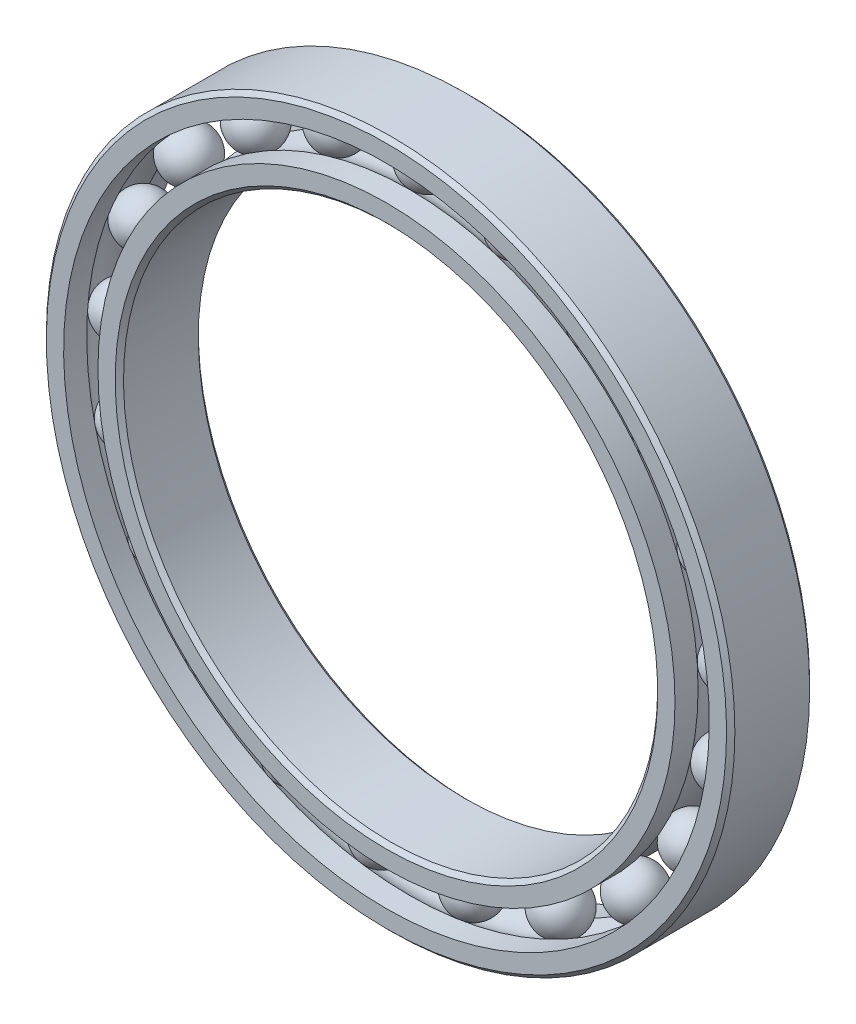
SolidWorks part; units mm, degrees
ref_plane "Front Plane" through (0, 0, 0) normal (0, 0, 1) x (1, 0, 0)
ref_plane "Top Plane" through (0, 0, 0) normal (0, 1, 0) x (1, 0, 0)
ref_plane "Right Plane" through (0, 0, 0) normal (1, 0, 0) x (0, 0, -1)
sketch "Sketch1" plane through (0, 0, 0) normal (0, 0, 1) x (1, 0, 0)
  circle A0 centre (0, 0) radius 29
  circle A1 centre (0, 0) radius 22.5
  dimension "OD" = 58
  dimension "ID" = 45
  dimension "For Shaft Diameter" = 45
  dimension "For Housing ID" = 58
sketch "Sketch5" plane through (0, 0, 0) normal (1, 0, 0) x (0, 0, -1)
  line L0 (-3.5, 0) -> (3.5, 0) construction
  line L1 (0, 29) -> (0, -29) construction
  line L2 (3.15, 29) -> (-3.15, 29)
  line L3 (-3.15, 29) -> (-3.5, 28.65)
  line L4 (-3.5, 28.65) -> (-3.5, 27.1944)
  line L5 (-3.5, 27.1944) -> (-1.5556, 27.1944)
  line L6 (3.5, 27.1944) -> (1.5556, 27.1944)
  line L7 (3.5, 28.65) -> (3.5, 27.1944)
  line L8 (3.15, 29) -> (3.5, 28.65)
  line L9 (0, 29) -> (0, 25.75) construction
  line L10 (0, 25.75) -> (0, 22.5) construction
  line L11 (-2.1228, 25.75) -> (-3.5, 25.75) construction
  line L12 (2.6209, 24.331) -> (3.0019, 24.331) construction
  line L13 (-2.6209, 24.331) -> (-3.0019, 24.331) construction
  line L14 (-2.6209, 24.331) -> (-2.6209, 27.169) construction
  line L15 (-2.6209, 27.169) -> (-3.0019, 27.169) construction
  line L16 (-3.0019, 24.331) -> (-3.0019, 27.169) construction
  line L17 (-2.6209, 24.331) -> (-3.0019, 27.169) construction
  line L18 (-2.6209, 27.169) -> (-3.0019, 24.331) construction
  line L19 (3.0019, 24.331) -> (3.0019, 27.169) construction
  line L20 (2.6209, 27.169) -> (3.0019, 27.169) construction
  line L21 (2.6209, 24.331) -> (2.6209, 27.169) construction
  line L22 (0, 29) -> (0, -29) construction
  arc A0 (-1.5556, 27.1944) -> (1.5556, 27.1944) centre (0, 25.75) cw
  circle A1 centre (0, 25.75) radius 2.1228 construction
  point P14 (0, 22.5)
  point P15 (-2.8114, 25.75)
  dimension "D1" = 45
  dimension "D2" = 0.35
  dimension "D3" = 3.1111
  dimension "D4" = 1.4444
  dimension "D5" = 0.381
  dimension "D6" = 0.0254
  dimension "Width" = 7
sketch "Sketch6" plane through (0, 0, 0) normal (1, 0, 0) x (0, 0, -1)
  line L0 (3.15, 29) -> (3.5, 28.65) construction
  line L1 (3.5, 28.65) -> (3.5, 27.1944) construction
  line L2 (3.5, 27.1944) -> (1.5556, 27.1944) construction
  line L3 (-3.5, 27.1944) -> (-1.5556, 27.1944) construction
  line L4 (-3.5, 28.65) -> (-3.5, 27.1944) construction
  line L5 (-3.15, 29) -> (-3.5, 28.65) construction
  line L6 (3.15, 29) -> (-3.15, 29) construction
  line L7 (3.15, 29) -> (3.5, 28.65)
  line L8 (3.5, 28.65) -> (3.5, 27.1944)
  line L9 (3.5, 27.1944) -> (1.5556, 27.1944)
  line L10 (-3.5, 27.1944) -> (-1.5556, 27.1944)
  line L11 (-3.5, 28.65) -> (-3.5, 27.1944)
  line L12 (-3.15, 29) -> (-3.5, 28.65)
  line L13 (3.15, 29) -> (-3.15, 29)
  arc A0 (1.5556, 27.1944) -> (-1.5556, 27.1944) centre (0, 25.75) ccw construction
  arc A1 (1.5556, 27.1944) -> (-1.5556, 27.1944) centre (0, 25.75) ccw
revolve "Revolve5" add sketch "Sketch6" angle 360 about L0
sketch "Sketch3" plane through (0, 0, 0) normal (1, 0, 0) x (0, 0, -1)
  line L0 (-3.5, 24.3056) -> (-1.5556, 24.3056)
  line L1 (0, 29) -> (0, -29) construction
  line L2 (-3.5, 28.65) -> (-3.5, 27.1944) construction
  line L3 (-3.5, 24.3056) -> (-3.5, 22.85)
  line L4 (-3.15, 29) -> (-3.5, 28.65) construction
  line L5 (-3.5, 22.85) -> (-3.15, 22.5)
  line L6 (-3.15, 22.5) -> (3.15, 22.5)
  line L8 (3.15, 22.5) -> (3.5, 22.85)
  line L10 (3.5, 22.85) -> (3.5, 24.3056)
  line L11 (3.5, 24.3056) -> (1.5556, 24.3056)
  line L12 (3.15, 29) -> (3.15, -29) construction
  line L13 (3.15, 29) -> (3.5, 28.65) construction
  line L14 (3.5, -28.65) -> (3.5, 28.65) construction
  arc A0 (1.5556, 27.1944) -> (-1.5556, 27.1944) centre (0, 25.75) ccw construction
  arc A1 (1.5556, 24.3056) -> (-1.5556, 24.3056) centre (0, 25.75) cw
revolve "Revolve3" add sketch "Sketch3" angle 360 about L0
sketch "Sketch4" plane through (0, 0, 0) normal (1, 0, 0) x (0, 0, -1)
  line L0 (-2.1228, 25.75) -> (2.1228, 25.75)
  arc A2 (-2.1228, 25.75) -> (2.1228, 25.75) centre (0, 25.75) cw
  arc A3 (1.5556, 27.1944) -> (-1.5556, 27.1944) centre (0, 25.75) ccw construction
revolve "Revolve4" add sketch "Sketch4" angle 360 about L0
pattern_circular "CirPattern1" count 21 over 360 about axis through (0, 0, 0) along (0, 0, 1) of bodies 104
equation "\"D2@Sketch5\" = \"Width@Sketch5\" * .05"
equation "\"D3@Sketch5\" = \"Width@Sketch5\" / 2.25"
equation "\"D4@Sketch5\"=((\"OD@Sketch1\"-\"ID@Sketch1\")/2)/4.5"
